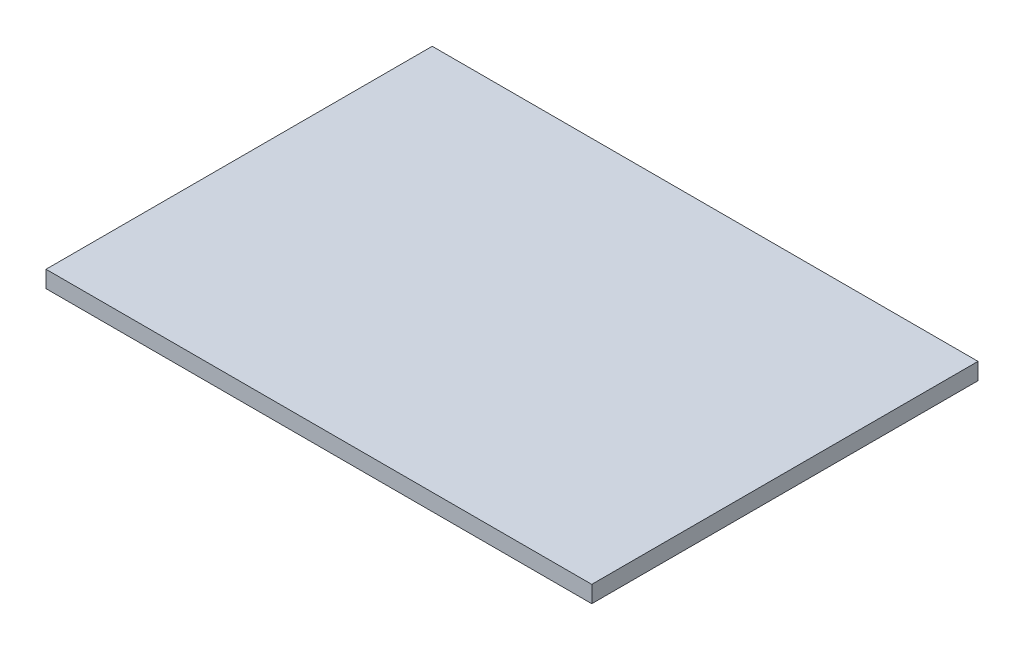
SolidWorks part; units mm, degrees
ref_plane "Front Plane" through (0, 0, 0) normal (0, 0, 1) x (1, 0, 0)
ref_plane "Top Plane" through (0, 0, 0) normal (0, 1, 0) x (1, 0, 0)
ref_plane "Right Plane" through (0, 0, 0) normal (1, 0, 0) x (0, 0, -1)
sketch "Sketch1" plane through (0, 0, 0) normal (0, 1, 0) x (0, 0, -1)
  line L1 (-23, -32.5) -> (23, -32.5)
  line L2 (-23, -32.5) -> (-23, 32.5)
  line L3 (-23, 32.5) -> (23, 32.5)
  line L4 (23, -32.5) -> (23, 32.5)
  line L5 (-23, -32.5) -> (23, 32.5) construction
  line L6 (-23, 32.5) -> (23, -32.5) construction
  point P0 (0, 0)
  dimension "D1" = 65
  dimension "D2" = 46
extrude "Boss-Extrude1" add sketch "Sketch1" along normal blind 2
